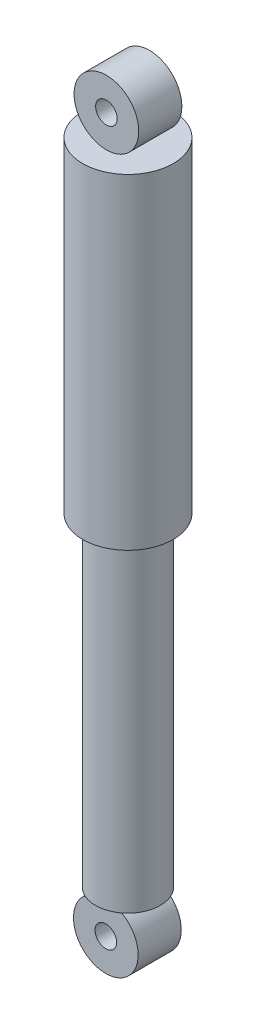
SolidWorks part; units mm, degrees
ref_plane "Płaszczyzna przednia" through (0, 0, 0) normal (0, 0, 1) x (1, 0, 0)
ref_plane "Płaszczyzna górna" through (0, 0, 0) normal (0, 1, 0) x (1, 0, 0)
ref_plane "Płaszczyzna prawa" through (0, 0, 0) normal (1, 0, 0) x (0, 0, -1)
sketch "Szkic1" plane through (0, 0, 0) normal (0, 0, 1) x (1, 0, 0)
  circle A0 centre (0, 0) radius 15
  dimension "D1" = 30
extrude "Dodanie-wyciągnięcie1" add sketch "Szkic1" along normal blind 20
sketch "Szkic2" plane through (0, 0, 20) normal (0, 0, 1) x (1, 0, 0)
  circle A0 centre (0, 0) radius 5
  dimension "D1" = 10
extrude "Wytnij-wyciągnięcie1" cut sketch "Szkic2" against normal blind 20
ref_plane "Płaszczyzna2" through (0, 15, 0) normal (0, 1, 0) x (1, 0, 0)
sketch "Szkic3" plane through (0, 15, 0) normal (0, 1, 0) x (1, 0, 0)
  line L0 (-5, -20) -> (5, -20) construction
  circle A0 centre (0.2789, -10) radius 15
  dimension "D1" = 10
  dimension "D2" = 30
extrude "Dodanie-wyciągnięcie2" add sketch "Szkic3" along normal blind 150 separate body
sketch "Szkic4" plane through (0, 165, 0) normal (0, 1, 0) x (1, 0, 0)
  circle A0 centre (0.2789, -10) radius 15.5
  circle A1 centre (0.2789, -10) radius 21
  dimension "D1" = 31
  dimension "D2" = 42
extrude "Dodanie-wyciągnięcie3" add sketch "Szkic4" along normal blind 150 separate body
sketch "Szkic6" plane through (0, 315, 0) normal (0, 1, 0) x (1, 0, 0)
  circle A0 centre (0.2789, -10) radius 21
extrude "Dodanie-wyciągnięcie4" add sketch "Szkic6" along normal blind 1
sketch "Szkic7" plane through (0, 0, 0) normal (0, 0, 1) x (1, 0, 0)
  line L0 (0.2789, 316) -> (0.2789, 331)
  line L1 (21.2789, 316) -> (-20.7211, 316) construction
  circle A0 centre (0.2789, 331) radius 15
  circle A1 centre (0.2789, 331) radius 5
  dimension "D2" = 10
  dimension "D1" = 15
extrude "Dodanie-wyciągnięcie5" add sketch "Szkic7" along normal blind 20 separate body
